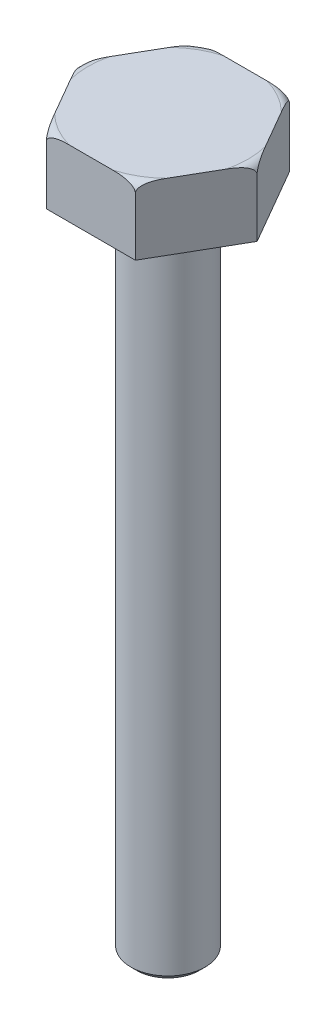
SolidWorks part; units mm, degrees
ref_plane "Front Plane" through (0, 0, 0) normal (0, 0, 1) x (1, 0, 0)
ref_plane "Top Plane" through (0, 0, 0) normal (0, 1, 0) x (1, 0, 0)
ref_plane "Right Plane" through (0, 0, 0) normal (1, 0, 0) x (0, 0, -1)
sketch "Sketch1" plane through (0, 0, 0) normal (0, 1, 0) x (1, 0, 0)
  circle A0 centre (0, 0) radius 25
  dimension "D1" = 50
extrude "Boss-Extrude1" add sketch "Sketch1" along normal blind 445
sketch "Sketch2" plane through (0, 445, 0) normal (0, 1, 0) x (1, 0, 0)
  line L0 (-60.0444, 0) -> (60.0444, 0)
  line L1 (30.0222, 52) -> (-30.0222, 52)
  line L2 (-30.0222, 52) -> (-60.0444, 0)
  line L3 (-60.0444, 0) -> (-30.0222, -52)
  line L4 (-30.0222, -52) -> (30.0222, -52)
  line L5 (30.0222, -52) -> (60.0444, 0)
  line L6 (60.0444, 0) -> (30.0222, 52)
  circle A0 centre (0, 0) radius 52 construction
  circle M8 centre (0, 0) radius 25
  dimension "D1" = 104
extrude "Boss-Extrude2" add sketch "Sketch2" along normal blind 45 contours L4 L5 L0 L3 M8 | L0 M8 | L0 L6 L1 L2 M8 | L0 M8
chamfer "Chamfer1" distance 4 angle 45 1 edges at (0, 0, 25)
sketch "Sketch4" plane through (0, 0, 0) normal (0, 0, 1) x (1, 0, 0)
  line L0 (0, 0) -> (0, 490)
  line L1 (-30.0222, 490) -> (30.0222, 490) construction
  line L2 (54.0444, 490) -> (54.0444, 484) construction
  line L3 (30.0222, 490) -> (60.0444, 490) construction
  line L4 (54.0444, 484) -> (60.0444, 484) construction
  line L5 (60.0444, 490) -> (60.0444, 445) construction
  line L6 (54.0444, 490) -> (54.0444, 495.9466)
  line L7 (54.0444, 495.9466) -> (66.8885, 495.9466)
  line L8 (66.8885, 495.9466) -> (66.8885, 484)
  line L9 (66.8885, 484) -> (60.0444, 484)
  arc A0 (54.0444, 490) -> (60.0444, 484) centre (54.0444, 484) cw
  dimension "D1" = 6
revolve "Cut-Revolve1" cut sketch "Sketch4" angle 360 about L0
